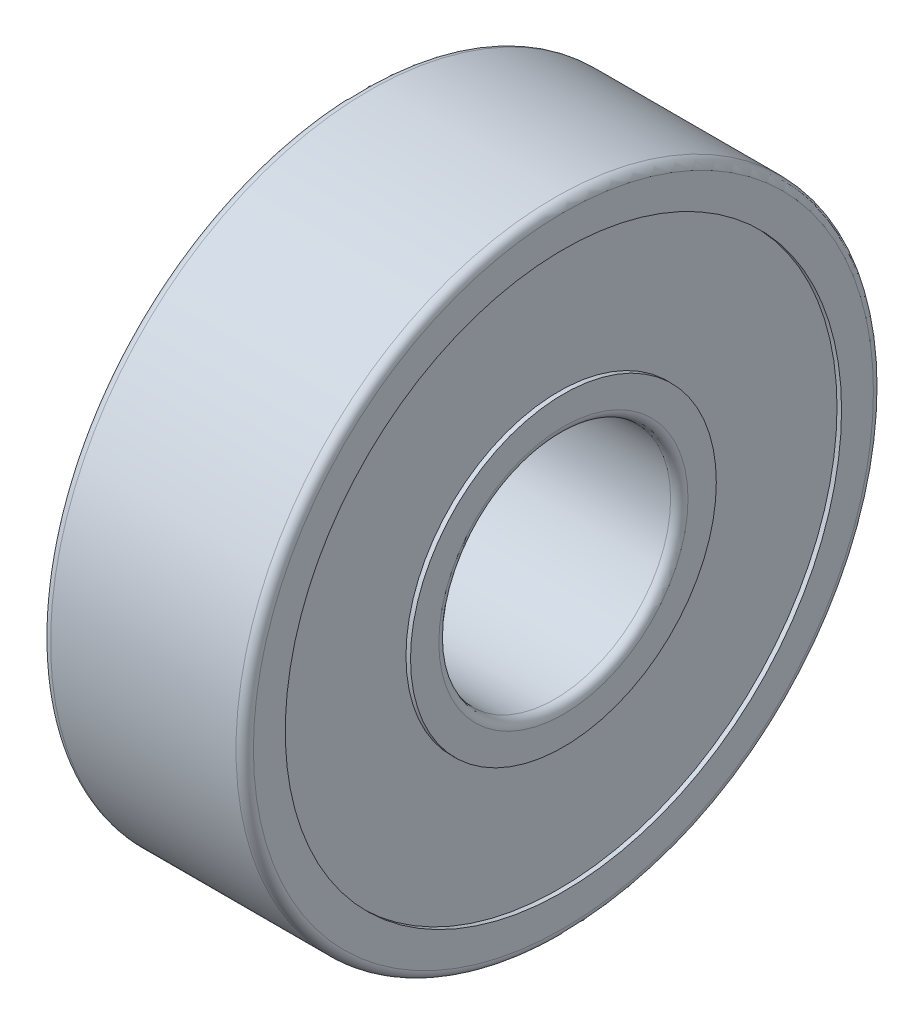
SolidWorks part; units mm, degrees
ref_plane "Front Plane" through (0, 0, 0) normal (0, 0, 1) x (1, 0, 0)
ref_plane "Top Plane" through (0, 0, 0) normal (0, 1, 0) x (1, 0, 0)
ref_plane "Right Plane" through (0, 0, 0) normal (1, 0, 0) x (0, 0, -1)
sketch "Sketch1" plane through (0, 0, 0) normal (0, 0, 1) x (1, 0, 0)
  line L0 (0, 0) -> (-7, 0) construction
  line L1 (-3.5, 0) -> (-3.5, 6.05) construction
  line L2 (-3.5, 0) -> (-3.5, 4) construction
  line L3 (-6.7, 4) -> (-0.3, 4)
  line L4 (0, 4.3) -> (0, 5.2771)
  line L5 (-0.61, 6.0271) -> (-2, 6.0271)
  line L6 (-3.5, 0) -> (-3.5, 7.35) construction
  line L7 (-6.69, 5.2771) -> (-7, 5.2771)
  line L8 (-0.61, 6.0271) -> (-0.61, 5.5771)
  line L9 (-0.31, 5.2771) -> (0, 5.2771)
  line L10 (-6.39, 6.0271) -> (-5, 6.0271)
  line L11 (-6.39, 6.0271) -> (-6.39, 5.5771)
  line L12 (-7, 4.3) -> (-7, 5.2771)
  line L13 (-3.5, 0) -> (-3.5, 11) construction
  line L14 (-0.3, 11) -> (-6.7, 11)
  line L15 (-7, 10.7) -> (-7, 9.6)
  line L16 (-7, 9.6) -> (-6.843, 9.6)
  line L17 (-6.843, 9.6) -> (-6.4426, 9.6) construction
  line L18 (-6.4426, 9.6) -> (-6.3024, 8.8048)
  line L19 (-0.6976, 8.8048) -> (-2.1276, 8.8048)
  line L20 (-0.5574, 9.6) -> (-0.6976, 8.8048)
  line L21 (-6.3024, 8.8048) -> (-4.8724, 8.8048)
  line L22 (0, 9.6) -> (-0.157, 9.6)
  line L23 (0, 10.7) -> (0, 9.6)
  line L28 (-3.5, 7.35) -> (-0.6956, 7.35) construction
  line L30 (-0.61, 6.0271) -> (-0.608, 6.0271) construction
  line L32 (-0.61, 5.5771) -> (-0.608, 5.5771) construction
  line L35 (-0.6956, 8.8048) -> (-0.2992, 8.8048) construction
  arc A0 (-2, 6.0271) -> (-5, 6.0271) centre (-3.5, 7.35) cw
  arc A1 (-0.61, 5.5771) -> (-0.31, 5.2771) centre (-0.31, 5.5771) ccw
  arc A2 (-0.3, 4) -> (0, 4.3) centre (-0.3, 4.3) ccw
  arc A3 (-6.7, 4) -> (-7, 4.3) centre (-6.7, 4.3) cw
  arc A4 (-6.39, 5.5771) -> (-6.69, 5.2771) centre (-6.69, 5.5771) cw
  circle A5 centre (-3.5, 7.35) radius 2 construction
  arc A6 (-6.843, 9.6) -> (-6.4426, 9.6) centre (-6.6428, 9.6) cw
  arc A7 (-6.7, 11) -> (-7, 10.7) centre (-6.7, 10.7) ccw
  arc A8 (-0.157, 9.6) -> (-0.5574, 9.6) centre (-0.3572, 9.6) ccw
  arc A9 (-0.3, 11) -> (0, 10.7) centre (-0.3, 10.7) cw
  arc A10 (-4.8724, 8.8048) -> (-2.1276, 8.8048) centre (-3.5, 7.35) cw
  point P16 (-0.61, 5.2771)
  point P36 (-7, 11)
  dimension "D8" = 1.39
  dimension "D5" = 0.3
  dimension "D6" = 0.3
  dimension "D10" = 2
  dimension "D13" = 5.2771
  dimension "D18" = 100
  dimension "D19" = 0.3
  dimension "D25" = 0.002
  dimension "D1" = 7
  dimension "D2" = 6.05
  dimension "D3" = 4
  dimension "D4" = 7
  dimension "D7" = 7.35
  dimension "D9" = 0.75
  dimension "D12" = 2.0271
  dimension "D14" = 2
  dimension "D15" = 11
  dimension "D16" = 1.4
  dimension "D17" = 0.157
  dimension "D21" = 0.4004
  dimension "D22" = 1.43
  dimension "D26" = 0.002
  dimension "D28" = 0.3964
revolve "Revolve1" add sketch "Sketch1" angle 360 about L0
sketch "Sketch2" plane through (0, 0, 0) normal (0, 1, 0) x (1, 0, 0)
  line L0 (-5.4845, 7.35) -> (-1.5155, 7.35)
  line L2 (-3.5, 9.35) -> (-3.5, 5.35) construction
  line L3 (-4.8724, 7.35) -> (-2.1276, 7.35) construction
  line L4 (-4.8724, 8.8048) -> (-4.8724, -8.8048) construction
  line L5 (-2.1276, 8.8048) -> (-2.1276, -8.8048) construction
  arc A0 (-2.1276, 8.8048) -> (-4.8724, 8.8048) centre (-3.5, 7.35) ccw construction
  arc A1 (-5, 6.0271) -> (-2, 6.0271) centre (-3.5, 7.35) ccw construction
  arc A2 (-5.4845, 7.35) -> (-1.5155, 7.35) centre (-3.5, 7.35) cw
  point P3 (-3.5, 7.35)
  dimension "D1" = 3.969
revolve "Revolve2" add sketch "Sketch2" angle 360 about L3
pattern_circular "CirPattern6" count 7 over 360 about axis through (0, 0, 0) along (1, 0, 0) of bodies 103
sketch "Sketch3" plane through (0, 0, 0) normal (0, 0, 1) x (1, 0, 0)
  line L0 (-0.5574, 9.6) -> (-0.6976, 8.8048) construction
  line L1 (-0.5574, 9.6) -> (-0.6976, 8.8048)
  line L2 (-0.61, 5.5771) -> (-0.61, 6.0271)
  line L3 (-0.61, 6.0271) -> (-0.6976, 8.8048)
  line L4 (-0.157, 9.6) -> (-0.157, 5.2771)
  line L5 (-0.157, 9.6) -> (-0.157, -9.6) construction
  line L6 (-0.157, 5.2771) -> (-0.31, 5.2771)
  arc A0 (-0.157, 9.6) -> (-0.5574, 9.6) centre (-0.3572, 9.6) ccw construction
  arc A1 (-0.61, 5.5771) -> (-0.31, 5.2771) centre (-0.31, 5.5771) ccw construction
  arc A2 (-0.157, 9.6) -> (-0.5574, 9.6) centre (-0.3572, 9.6) ccw
  arc A3 (-0.61, 5.5771) -> (-0.31, 5.2771) centre (-0.31, 5.5771) ccw
revolve "Revolve3" add sketch "Sketch3" angle 360
sketch "Sketch4" plane through (-7, 0, 0) normal (-1, 0, 0) x (0, 0, 1)
  line L0 (0, 0) -> (-0.0597, 6.8447) construction
  arc A0 (4.0209, 8.9371) -> (-4.1763, 8.8656) centre (0, 0) ccw construction
  text T0 "SKF 608 - 2RSH/C3" font "Century Gothic" height 0.65
extrude "Cut-Extrude2" cut sketch "Sketch4" against normal blind 0.02
